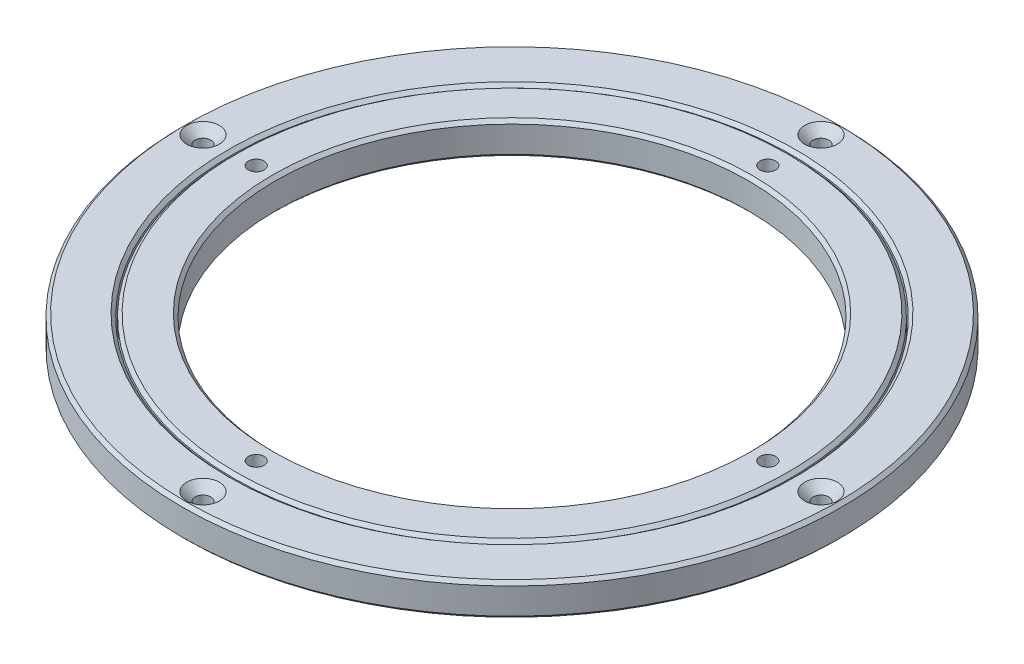
SolidWorks part; units mm, degrees
ref_plane "Front Plane" through (0, 0, 0) normal (0, 0, 1) x (1, 0, 0)
ref_plane "Top Plane" through (0, 0, 0) normal (0, 1, 0) x (1, 0, 0)
ref_plane "Right Plane" through (0, 0, 0) normal (1, 0, 0) x (0, 0, -1)
sketch "Sketch1" plane through (0, 0, 0) normal (0, 1, 0) x (1, 0, 0)
  circle A0 centre (0, 0) radius 72.375
  circle A1 centre (0, 0) radius 85.875
  circle A2 centre (0, 0) radius 85.475
  circle A3 centre (0, 0) radius 100.975
  dimension "D1" = 144.75
  dimension "D2" = 28.6
  dimension "D3" = 13.5
  dimension "D4" = 15.5
  dimension "D5" = 201.95
extrude "Boss-Extrude1" add sketch "Sketch1" along normal blind 10 contours A3 A1 | A2 A0
chamfer "Chamfer1" distance 1 angle 45 3 edges at (0, 10, 85.475) (0, 0, 72.375) (0, 10, 72.375)
chamfer "Chamfer2" distance 1 angle 45 4 edges at (0, 0, 100.975) (0, 10, 100.975) (0, 0, 85.875) (0, 10, 85.875)
sketch "Sketch2" plane through (0, 10, 0) normal (0, 1, 0) x (1, 0, 0)
  circle A0 centre (0, 0) radius 100.975 construction
  circle A1 centre (0, 0) radius 100.975
  circle A2 centre (0, 0) radius 94.675 construction
  point P0 (94.675, 0)
  point P10 (0, -94.675)
  point P12 (-94.675, 0)
  point P14 (0, 94.675)
  dimension "D1" = 6.3
hole_wizard "CSK for M4 Flat Head Machine Screw1" positions "Sketch2" profile "Sketch4" countersink size "M4" standard "ANSI Metric" end condition through all
sketch "Sketch4" plane through (94.675, 10, 0) normal (1, 0, 0) x (0, 0, 1)
  line L0 (0, 0) -> (0, 10)
  line L1 (0, 10) -> (2.4, 10)
  line L2 (2.4, 10) -> (2.4, 2.6)
  line L3 (2.4, 2.6) -> (5, 0)
  line L5 (5, 0) -> (0, 0)
  line L6 (-2.4, 2.6) -> (-5, 0) construction
  line L11 (0, -6.35) -> (0, 107.95) construction
  dimension "Thru Hole Dia." = 4.8
  dimension "Thru Hole Depth" = 10
  dimension "Near C'Sink Dia." = 10
  dimension "Near C'Sink Angle" = 90
hole_wizard "CSK for M4 Flat Head Machine Screw2" positions "Sketch5" profile "Sketch6" countersink size "M4" standard "ANSI Metric" end condition through all
sketch "Sketch5" plane through (0, 0, 0) normal (0, -1, 0) x (-1, 0, 0)
  circle A0 centre (0, 0) radius 78.375
  circle A1 centre (0, 0) radius 72.375 construction
  circle A2 centre (0, 0) radius 72.375
  point P8 (-78.375, 0)
  point P10 (0, 78.375)
  point P12 (78.375, 0)
  point P14 (0, -78.375)
  dimension "D1" = 6
sketch "Sketch6" plane through (0, 0, 78.375) normal (1, 0, 0) x (0, 0, -1)
  line L0 (0, 0) -> (0, 10)
  line L1 (0, 10) -> (2.4, 10)
  line L2 (2.4, 10) -> (2.4, 2.6)
  line L3 (2.4, 2.6) -> (5, 0)
  line L5 (5, 0) -> (0, 0)
  line L6 (-2.4, 2.6) -> (-5, 0) construction
  line L11 (0, -6.35) -> (0, 107.95) construction
  dimension "Thru Hole Dia." = 4.8
  dimension "Thru Hole Depth" = 10
  dimension "Near C'Sink Dia." = 10
  dimension "Near C'Sink Angle" = 90
